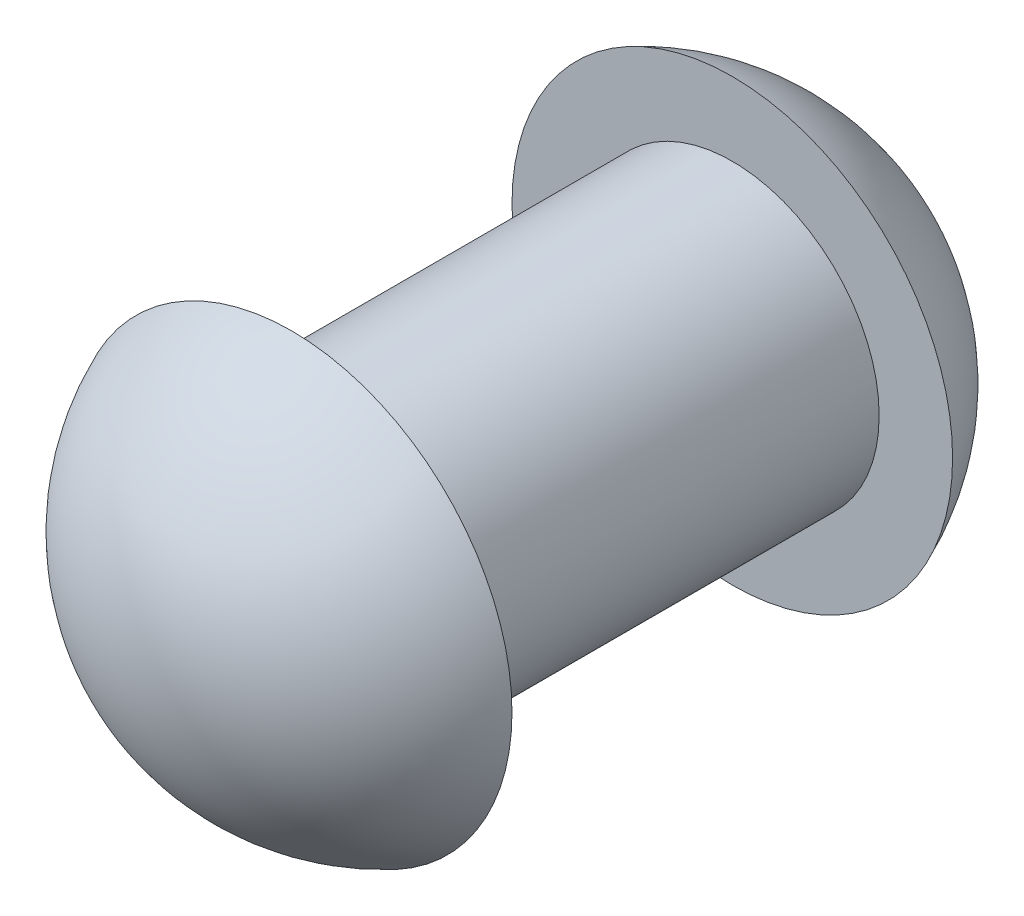
SolidWorks part; units mm, degrees
ref_plane "前视基准面" through (0, 0, 0) normal (0, 0, 1) x (1, 0, 0)
ref_plane "上视基准面" through (0, 0, 0) normal (0, 1, 0) x (1, 0, 0)
ref_plane "右视基准面" through (0, 0, 0) normal (1, 0, 0) x (0, 0, -1)
sketch "草图1" plane through (0, 0, 0) normal (0, 1, 0) x (1, 0, 0)
  line L0 (0, 2.5) -> (0, -2.5)
  line L1 (1.5, 1.5) -> (1, 1.5)
  line L2 (1, 1.5) -> (1, -1.5)
  line L3 (1, -1.5) -> (1.5, -1.5)
  arc A0 (0, 2.5) -> (1.5, 1.5) centre (0, 0.875) cw
  arc A1 (1.5, -1.5) -> (0, -2.5) centre (0, -0.875) cw
  point P3 (0, 0)
  point P10 (1, 0)
  dimension "D1" = 0.5
  dimension "D2" = 1
  dimension "D3" = 3
  dimension "D4" = 5
revolve "旋转1" add sketch "草图1" angle 360 about L0
